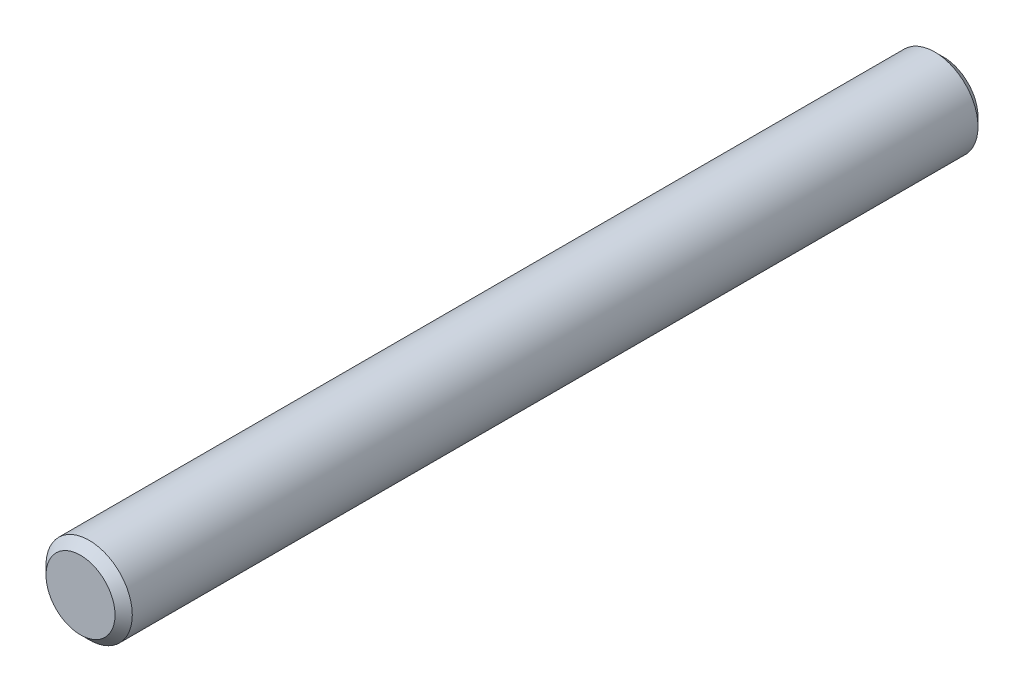
SolidWorks part; units mm, degrees
ref_plane "Front Plane" through (0, 0, 0) normal (0, 0, 1) x (1, 0, 0)
ref_plane "Top Plane" through (0, 0, 0) normal (0, 1, 0) x (1, 0, 0)
ref_plane "Right Plane" through (0, 0, 0) normal (1, 0, 0) x (0, 0, -1)
sketch "Sketch1" plane through (0, 0, 0) normal (0, 0, 1) x (1, 0, 0)
  circle A0 centre (0, 0) radius 0.635
  dimension "D1" = 1.27
extrude "Extrude1" add sketch "Sketch1" along normal mid plane 12.7
chamfer "Chamfer1" distance 0.127 angle 45 2 edges at (0.635, 0, -6.35) (0.635, 0, 6.35)
